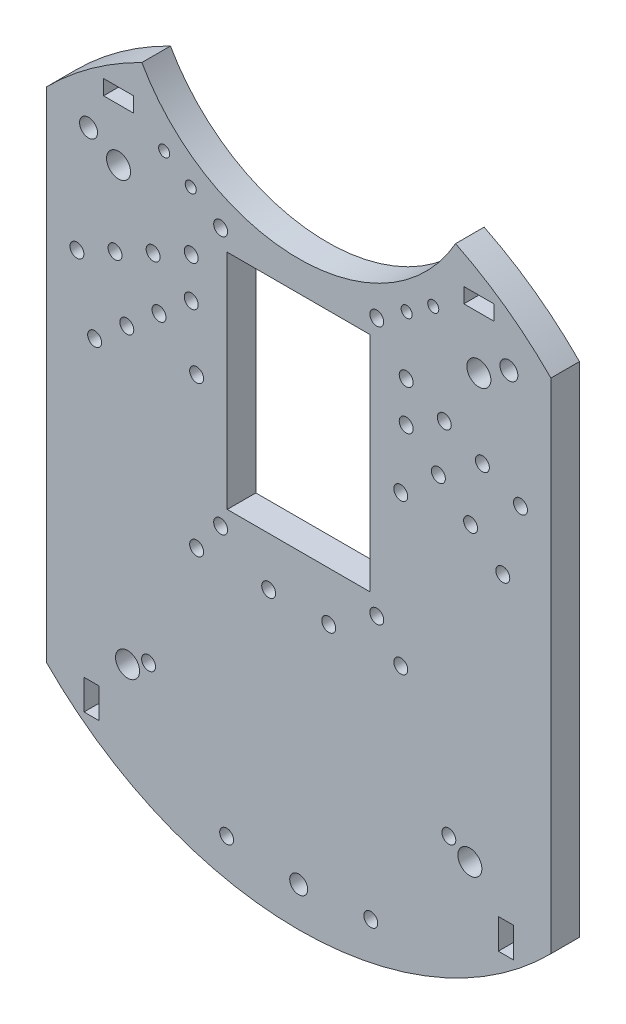
SolidWorks part; units mm, degrees
ref_plane "Front Plane" through (0, 0, 0) normal (0, 0, 1) x (1, 0, 0)
ref_plane "Top Plane" through (0, 0, 0) normal (0, 1, 0) x (1, 0, 0)
ref_plane "Right Plane" through (0, 0, 0) normal (1, 0, 0) x (0, 0, -1)
sketch "Sketch1" plane through (0, 0, 0) normal (0, 0, 1) x (1, 0, 0)
  line L0 (0, 47.9049) -> (0, -75) construction
  line L1 (-53.34, 0) -> (53.34, 0) construction
  line L5 (-53.34, 52.7242) -> (-53.34, -52.7242)
  line L22 (53.34, 52.7242) -> (53.34, -52.7242)
  arc A0 (-33.1727, 67.265) -> (-53.34, 52.7242) centre (0, 0) ccw
  arc A1 (-33.1727, 67.265) -> (33.1727, 67.265) centre (0, 86.0049) ccw
  circle A2 centre (0, -66.675) radius 1.8987
  circle A3 centre (-44.45, 49.6966) radius 1.8987
  circle A4 centre (44.45, 49.6966) radius 1.8986
  circle A5 centre (-21.59, -15.875) radius 1.4732
  circle A6 centre (-6.35, -15.875) radius 1.4732
  circle A7 centre (6.35, -15.875) radius 1.4732
  circle A8 centre (-15.24, -65.475) radius 1.4732
  circle A9 centre (15.24, -65.475) radius 1.4732
  circle A12 centre (21.59, -15.875) radius 1.4732
  circle A13 centre (6.35, 15.875) radius 1.4732
  circle A14 centre (-6.35, 15.875) radius 1.4732
  circle A15 centre (21.59, 15.875) radius 1.4732
  circle A18 centre (-21.59, 15.875) radius 1.4732
  arc A29 (-53.34, -52.7242) -> (53.34, -52.7242) centre (0, 0) ccw
  arc A30 (53.34, 52.7242) -> (33.1727, 67.265) centre (0, 0) ccw
  circle A31 centre (0, 0) radius 66.675 construction
  point P1 (-53.34, 0)
  point P50 (0, -65.475)
  dimension "D1" = 150
  dimension "D8" = 3.7973
  dimension "D12" = 133.35
  dimension "D11" = 3.7973
  dimension "D20" = 31.75
  dimension "D19" = 2.9464
  dimension "D9" = 2.9464
  dimension "D2" = 66.3453
  dimension "D3" = 38.1
  dimension "D4" = 44.45
  dimension "D6" = 53.34
  dimension "D7" = 0
  dimension "D13" = 15.875
  dimension "D14" = 9.525
  dimension "D18" = 0
  dimension "D23" = 15.24
  dimension "D10" = 15.24
extrude "Boss-Extrude3" add sketch "Sketch1" along normal blind 6.0452
sketch "Sketch7" plane through (0, 0, 6.0452) normal (0, 0, 1) x (1, 0, 0)
  line L0 (-34.925, -41.98) -> (34.925, -41.98) construction
  line L1 (-34.925, -61.03) -> (-34.925, -22.93) construction
  line L2 (-34.925, -61.03) -> (34.925, -61.03) construction
  line L3 (34.925, -61.03) -> (34.925, -22.93) construction
  line L4 (-34.925, -22.93) -> (34.925, -22.93) construction
  line L5 (0, -61.03) -> (0, -22.93) construction
  line L6 (-28.575, -55.7849) -> (-28.575, -28.1751) construction
  line L7 (-28.575, -55.7849) -> (28.575, -55.7849) construction
  line L8 (28.575, -55.7849) -> (28.575, -28.1751) construction
  line L9 (-28.575, -28.1751) -> (28.575, -28.1751) construction
  line L10 (-28.575, -55.7849) -> (28.575, -28.1751) construction
  line L11 (28.575, -55.7849) -> (-28.575, -28.1751) construction
  line L12 (0, 47.9049) -> (0, -75) construction
  circle A0 centre (-31.75, -41.98) radius 1.4732
  circle A1 centre (31.75, -41.98) radius 1.4732
  arc A2 (-33.1727, 67.265) -> (33.1727, 67.265) centre (0, 86.0049) ccw construction
  arc A3 (-53.34, -52.7242) -> (53.34, -52.7242) centre (0, 0) ccw construction
  point P0 (0, -41.98)
  dimension "D1" = 69.85
  dimension "D2" = 57.15
  dimension "D3" = 27.6098
  dimension "D4" = 3.175
  dimension "D5" = 38.1
  dimension "D6" = 33.02
extrude "Cut-Extrude2" cut sketch "Sketch7" against normal through all
sketch "Sketch9" plane through (0, 0, 6.0452) normal (0, 0, 1) x (1, 0, 0)
  line L1 (-15.113, 41.5549) -> (15.113, 41.5549)
  line L2 (-15.113, 41.5549) -> (-15.113, -5.5621)
  line L3 (-15.113, -5.5621) -> (15.113, -5.5621)
  line L4 (15.113, 41.5549) -> (15.113, -5.5621)
  line L5 (-15.113, 17.9964) -> (15.113, 17.9964) construction
  line L6 (0, 47.8414) -> (0, -11.8486) construction
  line L7 (0, 47.9049) -> (0, -75) construction
  line L8 (-19.05, 47.8414) -> (19.05, 47.8414) construction
  line L9 (-19.05, 47.8414) -> (-19.05, -11.8486) construction
  line L10 (-19.05, -11.8486) -> (19.05, -11.8486) construction
  line L11 (19.05, 47.8414) -> (19.05, -11.8486) construction
  line L12 (-19.05, 17.9964) -> (19.05, 17.9964) construction
  arc A1 (-33.1727, 67.265) -> (33.1727, 67.265) centre (0, 86.0049) ccw construction
  arc A2 (-53.34, -52.7242) -> (53.34, -52.7242) centre (0, 0) ccw construction
  circle A3 centre (-16.51, 45.3014) radius 1.4732
  circle A4 centre (16.51, 45.3014) radius 1.4732
  circle A5 centre (-16.51, -9.3086) radius 1.4732
  circle A6 centre (16.51, -9.3086) radius 1.4732
  point P6 (0, 17.9964)
  dimension "D6" = 2.9464
  dimension "D7" = 5.08
  dimension "D8" = 5.08
  dimension "D1" = 30.226
  dimension "D2" = 47.117
  dimension "D3" = 6.35
  dimension "D4" = 59.69
  dimension "D5" = 38.1
extrude "Cut-Extrude3" cut sketch "Sketch9" against normal blind 14.732
sketch "Sketch10" plane through (0, 0, 6.0452) normal (0, 0, 1) x (1, 0, 0)
  line L0 (0, 47.9049) -> (0, -75) construction
  line L2 (-41.275, 60.2874) -> (-34.925, 60.2874)
  line L3 (-41.275, 60.2874) -> (-41.275, 57.1124)
  line L4 (-41.275, 57.1124) -> (-34.925, 57.1124)
  line L5 (-34.925, 60.2874) -> (-34.925, 57.1124)
  line L6 (-41.275, 60.2874) -> (-34.925, 57.1124) construction
  line L7 (-41.275, 57.1124) -> (-34.925, 60.2874) construction
  line L8 (34.925, 60.2874) -> (34.925, 57.1124)
  line L9 (41.275, 60.2874) -> (34.925, 60.2874)
  line L10 (41.275, 60.2874) -> (41.275, 57.1124)
  line L11 (41.275, 57.1124) -> (34.925, 57.1124)
  line L13 (-45.4025, -51.4542) -> (-42.2275, -51.4542)
  line L14 (-45.4025, -51.4542) -> (-45.4025, -57.8042)
  line L15 (-45.4025, -57.8042) -> (-42.2275, -57.8042)
  line L16 (-42.2275, -51.4542) -> (-42.2275, -57.8042)
  line L17 (-45.4025, -51.4542) -> (-42.2275, -57.8042) construction
  line L18 (-45.4025, -57.8042) -> (-42.2275, -51.4542) construction
  line L19 (45.4025, -57.8042) -> (42.2275, -51.4542) construction
  line L20 (45.4025, -51.4542) -> (42.2275, -57.8042) construction
  line L21 (42.2275, -51.4542) -> (42.2275, -57.8042)
  line L22 (45.4025, -57.8042) -> (42.2275, -57.8042)
  line L23 (45.4025, -51.4542) -> (45.4025, -57.8042)
  line L24 (45.4025, -51.4542) -> (42.2275, -51.4542)
  arc A0 (-33.1727, 67.265) -> (33.1727, 67.265) centre (0, 86.0049) ccw construction
  arc A1 (-53.34, -52.7242) -> (53.34, -52.7242) centre (0, 0) ccw construction
  circle A3 centre (-36.195, -44.4692) radius 2.54
  circle A4 centre (36.195, -44.4692) radius 2.54
  circle A5 centre (-38.1, 45.9999) radius 2.54
  circle A6 centre (38.1, 45.9999) radius 2.54
  point P8 (-38.1, 58.6999)
  point P19 (-43.815, -54.6292)
  point P30 (43.815, -54.6292)
  dimension "D8" = 5.08
  dimension "D10" = 5.08
  dimension "D1" = 3.175
  dimension "D2" = 6.35
  dimension "D3" = 38.1
  dimension "D4" = 10.795
  dimension "D5" = 43.815
  dimension "D6" = 1.905
  dimension "D7" = 7.62
  dimension "D9" = 12.7
  dimension "D11" = 10.16
extrude "Cut-Extrude4" cut sketch "Sketch10" against normal up to surface (6.0452 mm away) up to face at (17.9832, -9.3086, 0)
sketch "Sketch11" plane through (0, 0, 6.0452) normal (0, 0, 1) x (1, 0, 0)
  line L0 (-62.6209, 41.275) -> (-62.6209, -41.275) construction
  circle A0 centre (0, 0) radius 75 construction
  dimension "D2" = 150
  dimension "D1" = 82.55
sketch "Sketch12" plane through (0, 0, 6.0452) normal (0, 0, 1) x (1, 0, 0)
  line L0 (0, 47.9049) -> (0, -74.9486) construction
  line L1 (0, 47.9049) -> (53.34, 23.032) construction
  line L2 (53.34, -52.7242) -> (53.34, 52.7242) construction
  line L3 (15.113, -5.5621) -> (15.113, 41.5549) construction
  line L4 (0, 47.9049) -> (53.34, 3.1473) construction
  arc A0 (-33.1727, 67.265) -> (33.1727, 67.265) centre (0, 86.0049) ccw construction
  circle A1 centre (22.733, 37.3043) radius 1.4732
  circle A2 centre (30.7901, 33.5472) radius 1.4732
  circle A3 centre (38.8472, 29.7902) radius 1.4732
  circle A4 centre (46.9042, 26.0331) radius 1.4732
  circle A5 centre (22.733, 28.8296) radius 1.4732
  circle A6 centre (29.5431, 23.1152) radius 1.4732
  circle A7 centre (36.3533, 17.4009) radius 1.4732
  circle A8 centre (43.1634, 11.6865) radius 1.4732
  circle A9 centre (-43.1634, 11.6865) radius 1.4732
  circle A10 centre (-36.3533, 17.4009) radius 1.4732
  circle A11 centre (-29.5431, 23.1152) radius 1.4732
  circle A12 centre (-22.733, 28.8296) radius 1.4732
  circle A13 centre (-46.9042, 26.0331) radius 1.4732
  circle A14 centre (-38.8472, 29.7902) radius 1.4732
  circle A15 centre (-30.7901, 33.5472) radius 1.4732
  circle A16 centre (-22.733, 37.3043) radius 1.4732
  dimension "D2" = 2.9464
  dimension "D5" = 8.89
  dimension "D1" = 65
  dimension "D3" = 7.62
  dimension "D6" = 50
  dimension "D8" = 8.89
  dimension "D4" = 4
  dimension "D7" = 4
extrude "Cut-Extrude5" cut sketch "Sketch12" against normal up to surface (6.0452 mm away) up to face at (40.64, 45.9999, 0)
sketch "Sketch13" plane through (0, 0, 6.0452) normal (0, 0, 1) x (1, 0, 0)
  line L0 (0, 47.9049) -> (0, -75) construction
  line L7 (-22.9461, 55.5249) -> (-26.5812, 50.1335) construction
  line L8 (-28.2533, 59.1032) -> (-17.6389, 51.9466) construction
  line L9 (-28.2533, 59.1032) -> (-31.8884, 53.7117) construction
  line L10 (-31.8884, 53.7117) -> (-21.274, 46.5552) construction
  line L11 (-17.6389, 51.9466) -> (-21.274, 46.5552) construction
  line L12 (-28.2533, 59.1032) -> (-21.274, 46.5552) construction
  line L13 (-31.8884, 53.7117) -> (-17.6389, 51.9466) construction
  line L14 (15.113, 41.5549) -> (-15.113, 41.5549) construction
  circle A0 centre (0, 0) radius 75 construction
  circle A1 centre (22.8325, 49.6278) radius 1.1684
  circle A2 centre (-22.8325, 49.6278) radius 1.1684
  circle A3 centre (-28.4556, 53.4191) radius 1.1684
  arc A6 (-33.1727, 67.265) -> (33.1727, 67.265) centre (0, 86.0049) ccw construction
  circle A7 centre (28.4556, 53.4191) radius 1.1684
  point P11 (-24.7637, 52.8292)
  dimension "D4" = 2.3368
  dimension "D5" = 1.6764
  dimension "D6" = 3.3909
  dimension "D7" = 6.5024
  dimension "D8" = 12.8016
  dimension "D9" = 13.97
  dimension "D10" = 56.011
extrude "Cut-Extrude6" cut sketch "Sketch13" against normal up to surface (6.0452 mm away) up to face at (-21.2598, 37.3043, 0)
